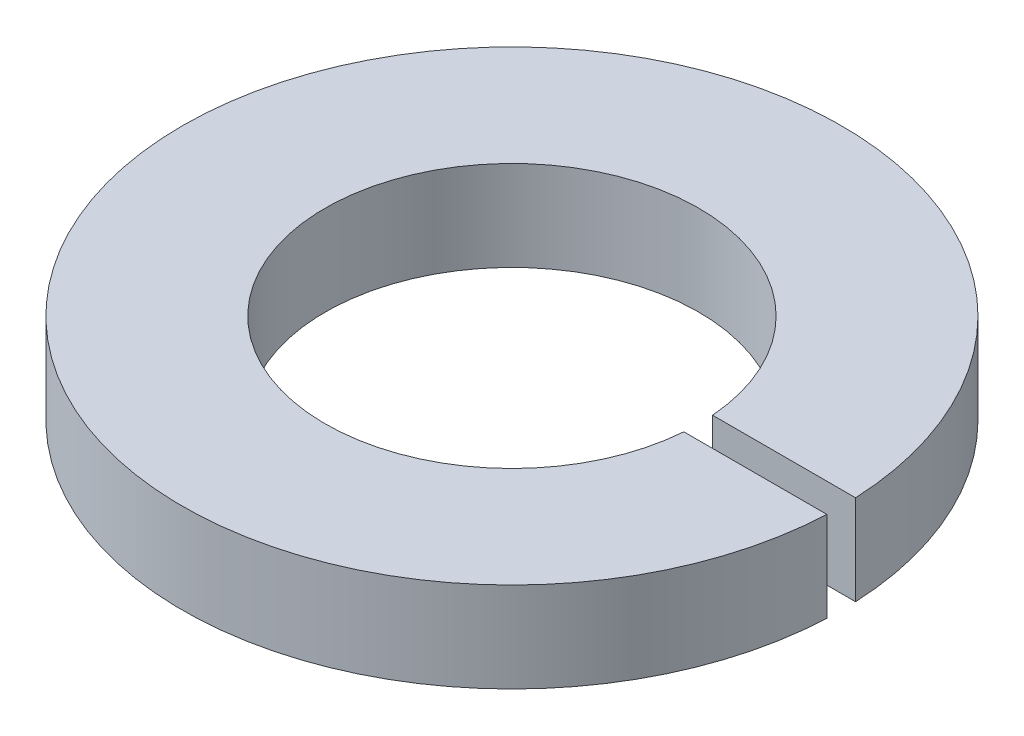
SolidWorks part; units mm, degrees
ref_plane "front" through (0, 0, 0) normal (0, 0, 1) x (1, 0, 0)
ref_plane "top" through (0, 0, 0) normal (0, 1, 0) x (1, 0, 0)
ref_plane "side" through (0, 0, 0) normal (1, 0, 0) x (0, 0, -1)
other "Configuration Table"
sketch "Sketch1" plane through (0, 0, 0) normal (0, 1, 0) x (1, 0, 0)
  circle A0 centre (0, 0) radius 4.953
  circle A1 centre (0, 0) radius 8.7376
  dimension "D1" = 17.4752
  dimension "D2" = 9.906
extrude "Base-Extrude" add sketch "Sketch1" along normal blind 2.3876
sketch "Sketch2" plane through (0, 2.3876, 0) normal (0, 1, 0) x (-1, 0, 0)
  line L0 (0, 0) -> (-14.5518, 0) construction
  line L1 (-8.7293, -0.381) -> (0, -0.381)
  line L2 (0, -0.381) -> (0, 0.381)
  line L3 (-8.7293, 0.381) -> (0, 0.381)
  circle A0 centre (0, 0) radius 8.7376 construction
  arc A1 (-8.7293, 0.381) -> (-8.7293, -0.381) centre (0, 0) ccw
  point P7 (-14.0898, 0)
  point P8 (0, 0)
  dimension "D1" = 0.762
extrude "Cut-Extrude1" cut sketch "Sketch2" against normal through all
